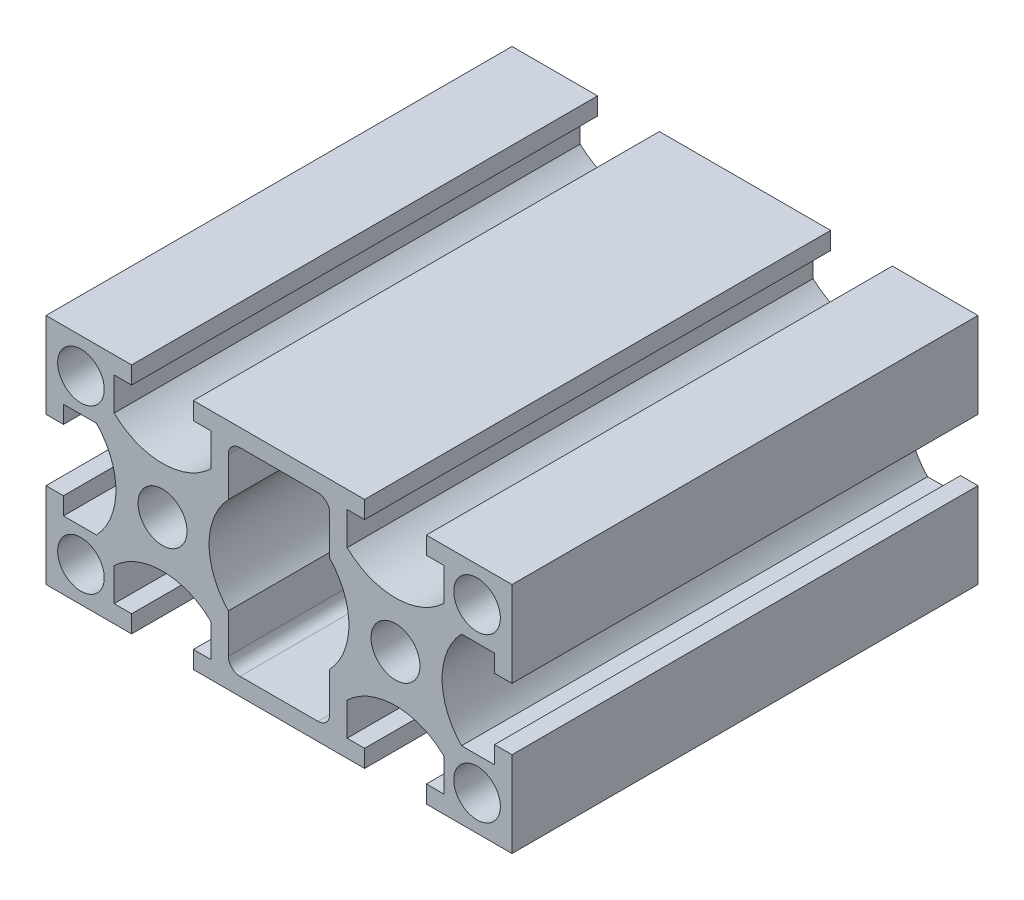
SolidWorks part; units mm, degrees
ref_plane "정면" through (0, 0, 0) normal (0, 0, 1) x (1, 0, 0)
ref_plane "윗면" through (0, 0, 0) normal (0, 1, 0) x (1, 0, 0)
ref_plane "우측면" through (0, 0, 0) normal (1, 0, 0) x (0, 0, -1)
sketch "스케치1" plane through (0, 0, 0) normal (0, 0, 1) x (1, 0, 0)
  line L1 (-20, 10) -> (20, 10)
  line L2 (-20, 10) -> (-20, -10)
  line L3 (-20, -10) -> (20, -10)
  line L4 (20, 10) -> (20, -10)
  line L5 (-20, 10) -> (20, -10) construction
  line L6 (-20, -10) -> (20, 10) construction
  point P0 (0, 0)
  dimension "D1" = 40
  dimension "D2" = 20
extrude "보스-돌출1" add sketch "스케치1" along normal blind 40
sketch "스케치2" plane through (0, 0, 40) normal (0, 0, 1) x (1, 0, 0)
  line L0 (20, 10) -> (-20, 10) construction
  line L1 (0, -11) -> (0, 11) construction
  line L2 (-20, 10) -> (-20, -10) construction
  line L3 (-20, -10) -> (20, -10) construction
  line L4 (20, -10) -> (20, 10) construction
  circle A0 centre (-17, 7) radius 2
  circle A1 centre (-17, -7) radius 2
  circle A2 centre (17, -7) radius 2
  circle A3 centre (17, 7) radius 2
  circle A4 centre (0, 0) radius 6
  circle A5 centre (-10, 0) radius 2.1
  circle A6 centre (10, 0) radius 2.1
  dimension "D1" = 4
  dimension "D2" = 4
  dimension "D3" = 4
  dimension "D4" = 4
  dimension "D11" = 12
  dimension "D12" = 4.2
  dimension "D5" = 14
  dimension "D6" = 3
  dimension "D7" = 3
  dimension "D8" = 3
  dimension "D9" = 3
  dimension "D10" = 3
  dimension "D13" = 10
  dimension "D14" = 10
extrude "컷-돌출1" cut sketch "스케치2" against normal through all
sketch "스케치3" plane through (0, 0, 0) normal (0, 0, -1) x (-1, 0, 0)
  line L0 (-20, 2.65) -> (-20, -2.65)
  line L1 (-20, -10) -> (-20, 10) construction
  line L2 (-20, 2.65) -> (-18.5, 2.65)
  line L3 (-18.5, 2.65) -> (-18.5, 4.15)
  line L4 (-18.5, 4.15) -> (-15.6667, 4.15)
  line L5 (-20, -2.65) -> (-18.5, -2.65)
  line L6 (-18.5, -2.65) -> (-18.5, -4.15)
  line L7 (-18.5, -4.15) -> (-15.6667, -4.15)
  line L8 (-14.15, 8.5) -> (-14.15, 5.6667)
  line L9 (-5.85, 8.5) -> (-5.85, 5.6667)
  line L10 (-7.35, 8.5) -> (-5.85, 8.5)
  line L11 (-7.35, 10) -> (-7.35, 8.5)
  line L12 (-7.35, 10) -> (-12.65, 10)
  line L13 (-12.65, 10) -> (-12.65, 8.5)
  line L14 (-12.65, 8.5) -> (-14.15, 8.5)
  line L15 (22, 0) -> (-22, 0) construction
  line L16 (-12.65, -8.5) -> (-14.15, -8.5)
  line L17 (-12.65, -10) -> (-12.65, -8.5)
  line L18 (-7.35, -10) -> (-12.65, -10)
  line L19 (-7.35, -10) -> (-7.35, -8.5)
  line L20 (-7.35, -8.5) -> (-5.85, -8.5)
  line L21 (-5.85, -8.5) -> (-5.85, -5.6667)
  line L22 (-14.15, -8.5) -> (-14.15, -5.6667)
  line L23 (0, 11) -> (0, -11) construction
  line L24 (14.15, -8.5) -> (14.15, -5.6667)
  line L25 (5.85, -8.5) -> (5.85, -5.6667)
  line L26 (7.35, -8.5) -> (5.85, -8.5)
  line L27 (7.35, -10) -> (7.35, -8.5)
  line L28 (7.35, -10) -> (12.65, -10)
  line L29 (12.65, -10) -> (12.65, -8.5)
  line L30 (12.65, -8.5) -> (14.15, -8.5)
  line L31 (12.65, 8.5) -> (14.15, 8.5)
  line L32 (12.65, 10) -> (12.65, 8.5)
  line L33 (7.35, 10) -> (12.65, 10)
  line L34 (7.35, 10) -> (7.35, 8.5)
  line L35 (7.35, 8.5) -> (5.85, 8.5)
  line L36 (5.85, 8.5) -> (5.85, 5.6667)
  line L37 (14.15, 8.5) -> (14.15, 5.6667)
  line L38 (18.5, -4.15) -> (15.6667, -4.15)
  line L39 (18.5, -2.65) -> (18.5, -4.15)
  line L40 (20, -2.65) -> (18.5, -2.65)
  line L41 (18.5, 4.15) -> (15.6667, 4.15)
  line L42 (18.5, 2.65) -> (18.5, 4.15)
  line L43 (20, 2.65) -> (18.5, 2.65)
  line L44 (20, 2.65) -> (20, -2.65)
  arc A0 (-15.6667, 4.15) -> (-15.6667, -4.15) centre (-20, 0) cw
  arc A1 (-5.85, 5.6667) -> (-14.15, 5.6667) centre (-10, 10) cw
  arc A2 (-5.85, -5.6667) -> (-14.15, -5.6667) centre (-10, -10) ccw
  arc A3 (5.85, -5.6667) -> (14.15, -5.6667) centre (10, -10) cw
  arc A4 (5.85, 5.6667) -> (14.15, 5.6667) centre (10, 10) ccw
  arc A5 (15.6667, 4.15) -> (15.6667, -4.15) centre (20, 0) ccw
  point P5 (-20, 0)
  point P23 (-10, 0)
  point P62 (10, 0)
  point P63 (20, 0)
  dimension "D1" = 6
  dimension "D2" = 5.3
  dimension "D3" = 8.3
  dimension "D4" = 1.5
  dimension "D5" = 1.5
  dimension "D6" = 2
  dimension "D7" = 5.85
extrude "컷-돌출2" cut sketch "스케치3" against normal through all
sketch "스케치4" plane through (0, 0, 0) normal (0, 0, -1) x (-1, 0, 0)
  line L0 (-7.35, 10) -> (7.35, 10) construction
  line L1 (-3.35, 8.5) -> (3.35, 8.5)
  line L2 (-4.35, 7.5) -> (-4.35, -7.5)
  line L3 (-3.35, -8.5) -> (3.35, -8.5)
  line L4 (4.35, 7.5) -> (4.35, -7.5)
  line L5 (-4.35, 8.5) -> (4.35, -8.5) construction
  line L6 (-4.35, -8.5) -> (4.35, 8.5) construction
  line L7 (-5.85, 5.6667) -> (-5.85, 8.5) construction
  arc A0 (-4.35, -7.5) -> (-3.35, -8.5) centre (-3.35, -7.5) ccw
  arc A1 (3.35, -8.5) -> (4.35, -7.5) centre (3.35, -7.5) ccw
  arc A2 (3.35, 8.5) -> (4.35, 7.5) centre (3.35, 7.5) cw
  arc A3 (-3.35, 8.5) -> (-4.35, 7.5) centre (-3.35, 7.5) ccw
  point P0 (0, 0)
  dimension "D3" = 1
  dimension "D1" = 1.5
  dimension "D2" = 1.5
extrude "컷-돌출3" cut sketch "스케치4" against normal through all
